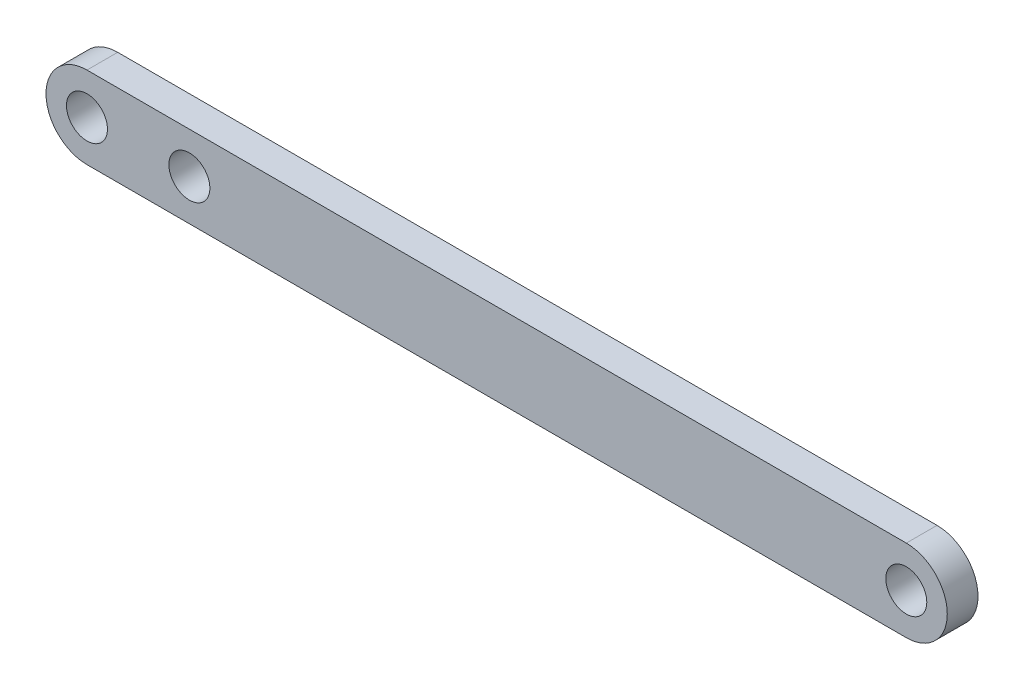
SolidWorks part; units mm, degrees
material "Zoltek Panex 33"
ref_plane "前视基准面" through (0, 0, 0) normal (0, 0, 1) x (1, 0, 0)
ref_plane "上视基准面" through (0, 0, 0) normal (0, 1, 0) x (1, 0, 0)
ref_plane "右视基准面" through (0, 0, 0) normal (1, 0, 0) x (0, 0, -1)
sketch "草图1" plane through (0, 0, 0) normal (0, 0, 1) x (1, 0, 0)
  line L1 (0, 0) -> (40, 0) construction
  line L2 (0, 2) -> (40, 2)
  line L3 (0, -2) -> (40, -2)
  arc A1 (0, 2) -> (0, -2) centre (0, 0) ccw
  arc A2 (40, -2) -> (40, 2) centre (40, 0) ccw
  circle A3 centre (40, 0) radius 1
  circle A4 centre (0, 0) radius 1
  circle A5 centre (5, 0) radius 1
  point P6 (20, 0)
  dimension "D1" = 2
  dimension "D3" = 2
  dimension "D4" = 2
  dimension "D5" = 2
  dimension "D2" = 40
  dimension "D6" = 5
extrude "凸台-拉伸1" add sketch "草图1" along normal blind 1.5
